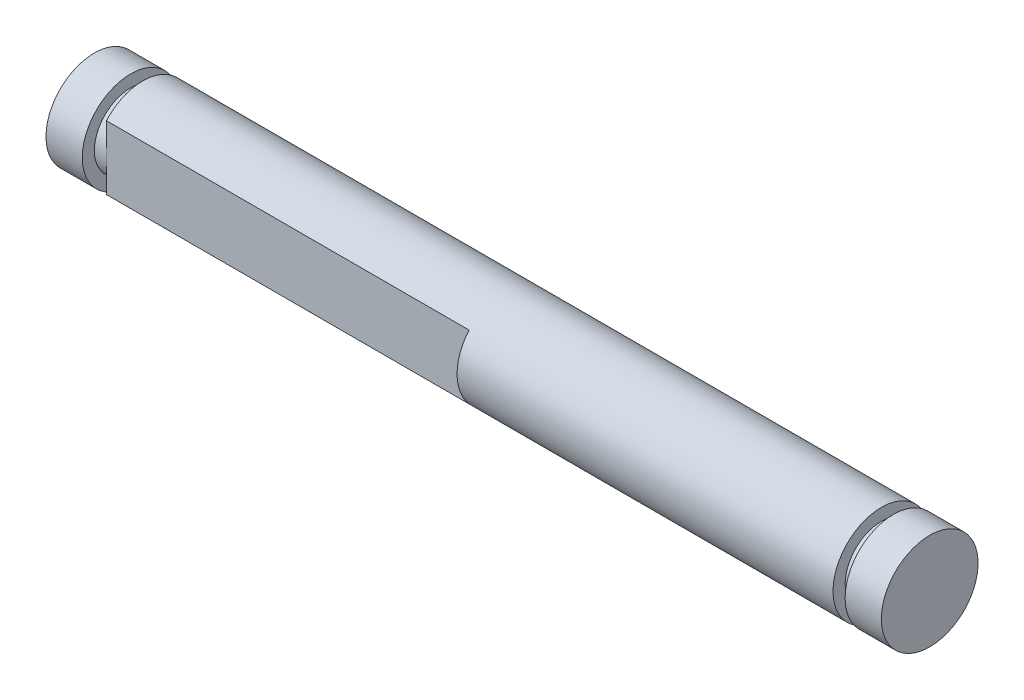
SolidWorks part; units mm, degrees
material "6061-T6 (SS)"
ref_plane "Alzado" through (0, 0, 0) normal (0, 0, 1) x (1, 0, 0)
ref_plane "Planta" through (0, 0, 0) normal (0, 1, 0) x (1, 0, 0)
ref_plane "Vista lateral" through (0, 0, 0) normal (1, 0, 0) x (0, 0, -1)
sketch "Croquis1" plane through (0, 0, 0) normal (0, 1, 0) x (1, 0, 0)
  line L0 (-34.55, 0) -> (34.55, 0) construction
  line L1 (-34.55, 0) -> (-34.55, 4)
  line L2 (-34.55, 4) -> (-31.55, 4)
  line L3 (-31.55, 4) -> (-31.55, 3)
  line L4 (-31.55, 3) -> (-30.55, 3)
  line L5 (-30.55, 3) -> (-30.55, 4)
  line L6 (-30.55, 4) -> (30.55, 4)
  line L7 (30.55, 4) -> (30.55, 3)
  line L8 (30.55, 3) -> (31.55, 3)
  line L9 (31.55, 3) -> (31.55, 4)
  line L10 (31.55, 4) -> (34.55, 4)
  line L11 (34.55, 4) -> (34.55, 0)
  line L12 (-34.55, 0) -> (34.55, 0)
  point P3 (0, 0)
  point P14 (-31.55, 3.5)
  point P20 (0, 4)
  dimension "D1" = 61.1
  dimension "D2" = 1
  dimension "D3" = 8
  dimension "D4" = 6
  dimension "D5" = 3
revolve "Revolución1" add sketch "Croquis1" angle 360 about L0
sketch "Croquis2" plane through (0, 0, 0) normal (0, 1, 0) x (1, 0, 0)
  line L1 (-30.55, -4) -> (-0.55, -4)
  line L2 (-30.55, -4) -> (-30.55, -3)
  line L3 (-30.55, -3) -> (-0.55, -3)
  line L4 (-0.55, -4) -> (-0.55, -3)
  dimension "D1" = 1
  dimension "D2" = 30
extrude "Cortar-Extruir1" cut sketch "Croquis2" against normal through all both and the other way through all
